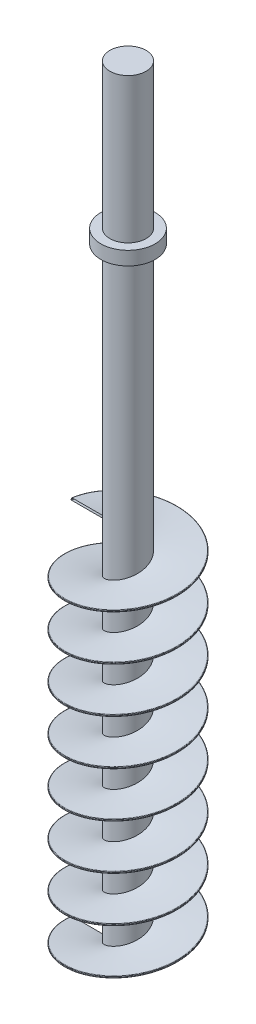
SolidWorks part; units mm, degrees
ref_plane "Front Plane" through (0, 0, 0) normal (0, 0, 1) x (1, 0, 0)
ref_plane "Top Plane" through (0, 0, 0) normal (0, 1, 0) x (1, 0, 0)
ref_plane "Right Plane" through (0, 0, 0) normal (1, 0, 0) x (0, 0, -1)
sketch "Sketch1" plane through (0, 0, 0) normal (0, 1, 0) x (1, 0, 0)
  circle A0 centre (0, 0) radius 4
  dimension "D1" = 8
extrude "Boss-Extrude1" add sketch "Sketch1" along normal blind 170
sketch "Sketch11" plane through (0, 0, 0) normal (0, -1, 0) x (1, 0, 0)
  circle A1 centre (0, 0) radius 4
  circle A2 centre (0, 0) radius 4
  dimension "D1" = 0
curve "Helix/Spiral1" pitch 10 height 80 turns 8
ref_plane "Plane1" through (-4, 0, 0) normal (0, 0.3697, 0.9292) x (1, 0, 0)
sketch "Sketch12" plane through (-4, 0, 0) normal (0, 0.3697, 0.9292) x (1, 0, 0)
  line L0 (4, 0) -> (-15.106, 0) construction
  line L1 (0.0368, 0.2) -> (-8.4, 0.2)
  line L2 (0.0368, -0.2) -> (-8.4, -0.2)
  line L3 (4, 0.2) -> (-15.106, 0.2) construction
  line L4 (4, -0.2) -> (-15.106, -0.2) construction
  line L5 (-8.5, 0.1) -> (-8.5, -0.1)
  arc A0 (-8.4, 0.2) -> (-8.5, 0.1) centre (-8.4, 0.1) ccw
  arc A1 (-8.4, -0.2) -> (-8.5, -0.1) centre (-8.4, -0.1) cw
  ellipse E1 centre (4, 0) end of major axis (8, 0) minor radius 1.4788
  ellipse E2 centre (4, 0) end of major axis (8, 0) minor radius 1.4788 (0.0368, 0.2) -> (0.0368, -0.2) ccw
  point P26 (-8.5, 0)
  dimension "D4" = 0.1
  dimension "D5" = 0.1
  dimension "D6" = 12.5
  dimension "D1" = 0.2
  dimension "D2" = 0.2
  dimension "D3" = 0
sketch "Sketch13" plane through (-4, 0, 0) normal (0, 0.3697, 0.9292) x (1, 0, 0)
surface "Surface-Sweep2"
sketch "Sketch16" plane through (0, 0, 0) normal (0, 0, 1) x (1, 0, 0)
  line L0 (0, 138) -> (6, 138)
  line L1 (6, 138) -> (6, 135)
  line L2 (6, 135) -> (0, 135)
  line L3 (0, 135) -> (0, 138)
  line L4 (4, 170) -> (-4, 170) construction
  line L5 (4, 0) -> (4, 170) construction
  dimension "D1" = 6
  dimension "D2" = 3
  dimension "D3" = 3
  dimension "D4" = 32
  dimension "D5" = 2
revolve "Revolve1" add sketch "Sketch16" angle 360 about L3
